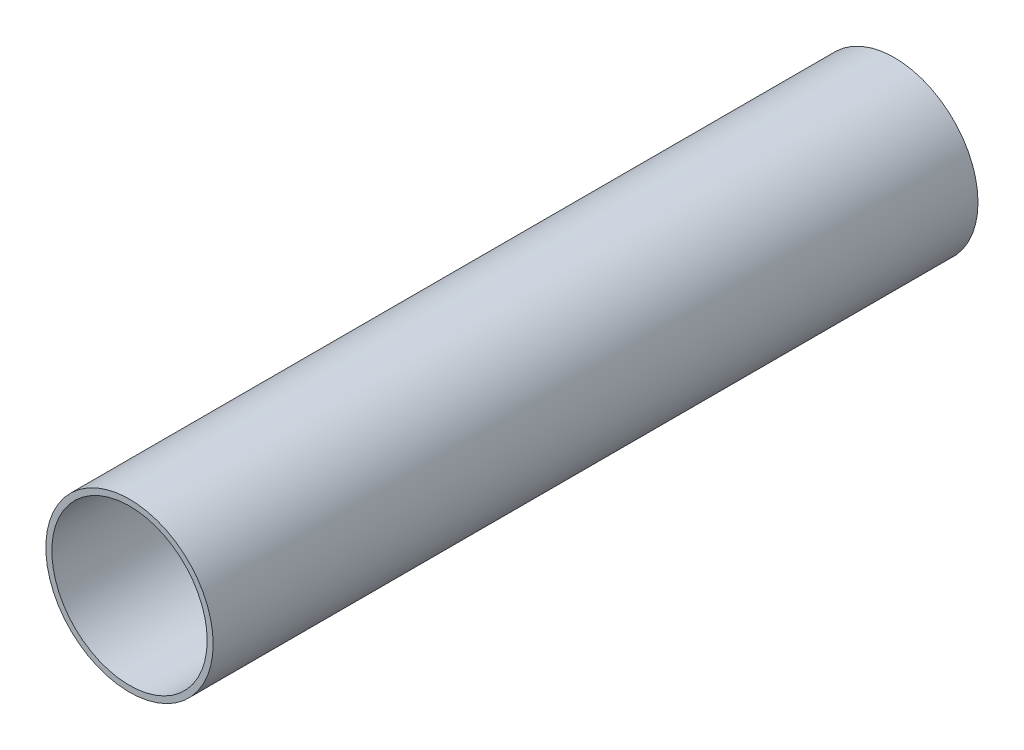
SolidWorks part; units mm, degrees
ref_plane "Front Plane" through (0, 0, 0) normal (0, 0, 1) x (1, 0, 0)
ref_plane "Top Plane" through (0, 0, 0) normal (0, 1, 0) x (1, 0, 0)
ref_plane "Right Plane" through (0, 0, 0) normal (1, 0, 0) x (0, 0, -1)
sketch "Sketch1" plane through (0, 0, 0) normal (0, 0, 1) x (1, 0, 0)
  circle A0 centre (0, 0) radius 22.225
  circle A1 centre (0, 0) radius 20.6375
  dimension "D1" = 44.45
  dimension "D2" = 1.5875
extrude "Boss-Extrude1" add sketch "Sketch1" along normal blind 203.2
scale "Scale1" scale about centroid uniform scaling yes scale factor 0.66
